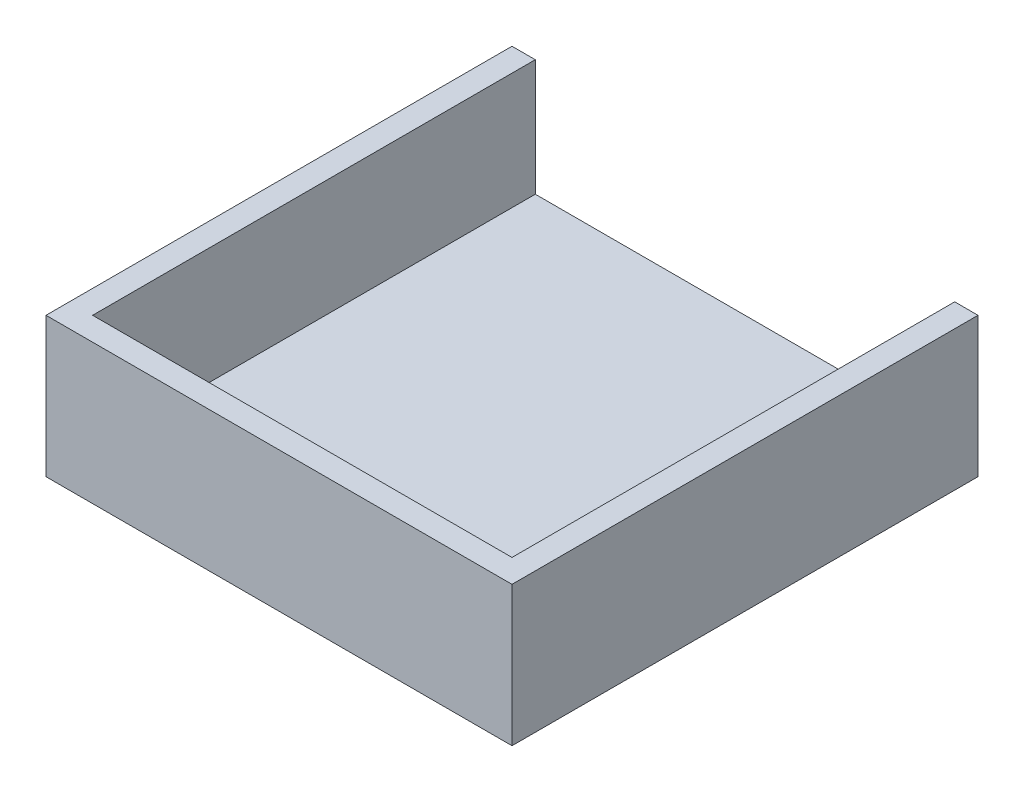
SolidWorks part; units mm, degrees
ref_plane "정면" through (0, 0, 0) normal (0, 0, 1) x (1, 0, 0)
ref_plane "윗면" through (0, 0, 0) normal (0, 1, 0) x (1, 0, 0)
ref_plane "우측면" through (0, 0, 0) normal (1, 0, 0) x (0, 0, -1)
sketch "스케치1" plane through (0, 0, 0) normal (0, 1, 0) x (1, 0, 0)
  line L1 (10, -10) -> (-10, -10)
  line L2 (10, -10) -> (10, 10)
  line L3 (10, 10) -> (-10, 10)
  line L4 (-10, -10) -> (-10, 10)
  line L5 (10, -10) -> (-10, 10) construction
  line L6 (10, 10) -> (-10, -10) construction
  point P0 (0, 0)
  dimension "D1" = 20
  dimension "D2" = 20
extrude "보스-돌출1" add sketch "스케치1" along normal blind 6
sketch "스케치3" plane through (0, 0, 0) normal (0, 1, 0) x (1, 0, 0)
  line L0 (-10, -10) -> (10, -10) construction
  line L1 (-9, 10) -> (9, 10)
  line L2 (-9, 10) -> (-9, -9)
  line L3 (-9, -9) -> (9, -9)
  line L4 (9, 10) -> (9, -9)
  line L5 (-10, 10) -> (-10, -10) construction
  dimension "D1" = 1
  dimension "D2" = 19
  dimension "D3" = 18
  dimension "D4" = 1
extrude "컷-돌출1" cut sketch "스케치3" along normal blind 6 from offset 1
sketch "스케치4" plane through (0, 0, 0) normal (0, 1, 0) x (1, 0, 0)
  line L1 (10, -10) -> (-10, -10)
  line L2 (10, -10) -> (10, 10)
  line L3 (10, 10) -> (-10, 10)
  line L4 (-10, -10) -> (-10, 10)
  line L5 (10, -10) -> (-10, 10) construction
  line L6 (10, 10) -> (-10, -10) construction
  point P0 (0, 0)
extrude "보스-돌출2" add sketch "스케치4" along normal blind 1 from offset 6 separate body
sketch "스케치7" plane through (0, 0, 0) normal (0, 1, 0) x (1, 0, 0)
  line L0 (-10, -10) -> (10, -10) construction
  line L1 (-7, 7) -> (7, 7)
  line L2 (-7, 7) -> (-7, -9)
  line L3 (-7, -9) -> (7, -9)
  line L4 (7, 7) -> (7, -9)
  line L5 (10, -10) -> (10, 10) construction
  dimension "D1" = 14
  dimension "D2" = 16
  dimension "D3" = 1
  dimension "D4" = 3
extrude "컷-돌출3" cut sketch "스케치7" against normal blind 1 from surface at 7 starting at face at (0, 7, 0)
sketch "스케치8" plane through (0, 7, 0) normal (0, 1, 0) x (1, 0, 0)
  line L4 (-10, 10) -> (-10, -10)
  line L5 (-10, -10) -> (10, -10)
  line L6 (10, -10) -> (10, 10)
  line L7 (10, 10) -> (-10, 10)
  line L8 (-10, 10) -> (-10, -10)
  line L9 (-10, -10) -> (10, -10)
  line L10 (10, -10) -> (10, 10)
  line L11 (10, 10) -> (-10, 10)
  dimension "D1" = 0
extrude "컷-돌출4" cut sketch "스케치8" against normal blind 1
